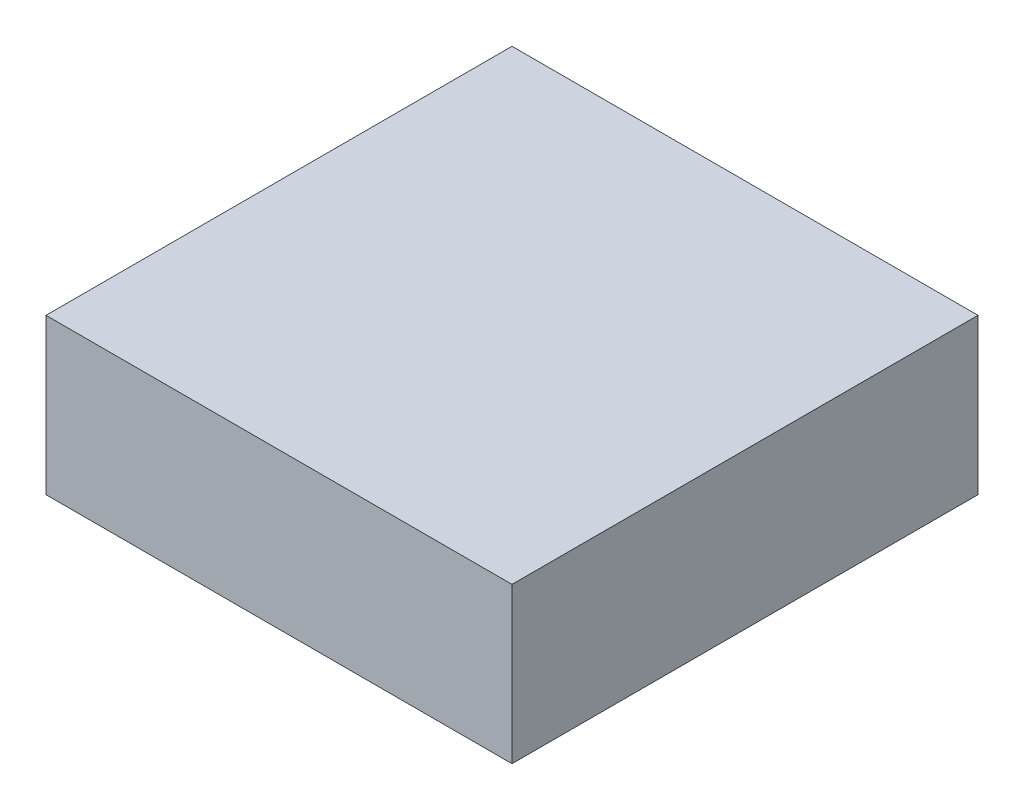
SolidWorks part; units mm, degrees
ref_plane "Front Plane" through (0, 0, 0) normal (0, 0, 1) x (1, 0, 0)
ref_plane "Top Plane" through (0, 0, 0) normal (0, 1, 0) x (1, 0, 0)
ref_plane "Right Plane" through (0, 0, 0) normal (1, 0, 0) x (0, 0, -1)
sketch "Sketch1" plane through (0, 0, 0) normal (0, 1, 0) x (1, 0, 0)
  line L1 (0, 0) -> (3, 0)
  line L2 (0, 0) -> (0, 3)
  line L3 (0, 3) -> (3, 3)
  line L4 (3, 0) -> (3, 3)
  dimension "D1" = 3
  dimension "D2" = 3
extrude "Boss-Extrude1" add sketch "Sketch1" along normal blind 1 contours L3 L4 L1 L2
